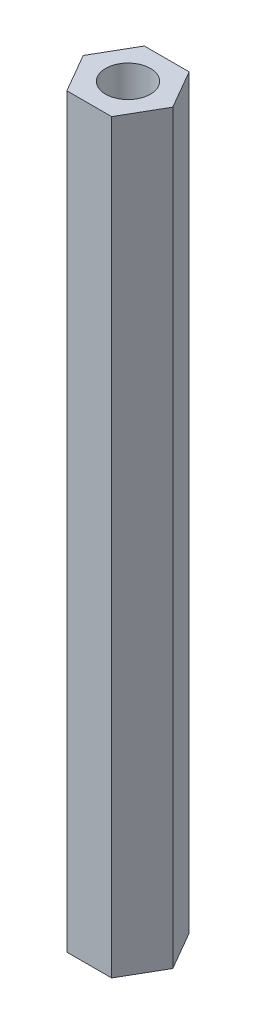
SolidWorks part; units mm, degrees
material "Stainless Steel (ferritic)"
ref_plane "Front Plane" through (0, 0, 0) normal (0, 0, 1) x (1, 0, 0)
ref_plane "Top Plane" through (0, 0, 0) normal (0, 1, 0) x (1, 0, 0)
ref_plane "Right Plane" through (0, 0, 0) normal (1, 0, 0) x (0, 0, -1)
other "Center of Mass"
sketch "Sketch1" plane through (0, 0, 0) normal (0, 1, 0) x (1, 0, 0)
  line L1 (3, 0) -> (1.5, 2.5981)
  line L2 (1.5, 2.5981) -> (-1.5, 2.5981)
  line L3 (-1.5, 2.5981) -> (-3, 0)
  line L4 (-3, 0) -> (-1.5, -2.5981)
  line L5 (-1.5, -2.5981) -> (1.5, -2.5981)
  line L6 (1.5, -2.5981) -> (3, 0)
  circle A0 centre (0, 0) radius 2.5981 construction
  circle A1 centre (0, 0) radius 1.5
  dimension "D2" = 3
  dimension "D1" = 6
extrude "Boss-Extrude1" add sketch "Sketch1" along normal blind 50
